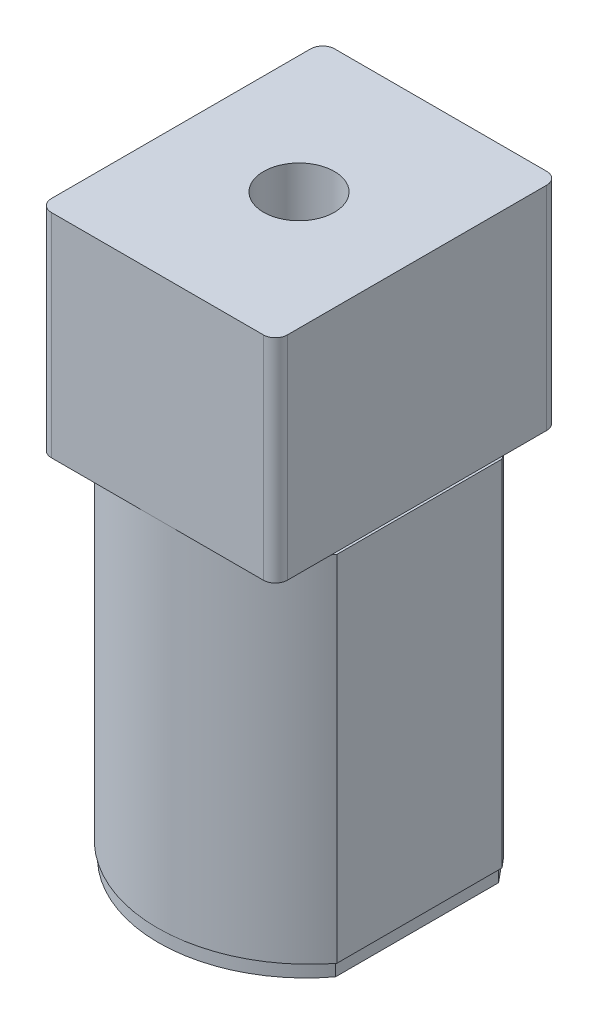
SolidWorks part; units mm, degrees
ref_plane "Front Plane" through (0, 0, 0) normal (0, 0, 1) x (1, 0, 0)
ref_plane "Top Plane" through (0, 0, 0) normal (0, 1, 0) x (1, 0, 0)
ref_plane "Right Plane" through (0, 0, 0) normal (1, 0, 0) x (0, 0, -1)
sketch "Sketch1" plane through (0, 0, 0) normal (0, 1, 0) x (1, 0, 0)
  line L0 (0, 6) -> (0, -6) construction
  line L1 (-5.1, -3.5) -> (5.1, -3.5)
  line L2 (-5.1, -3.5) -> (-5.1, 3.5)
  line L3 (-5.1, 3.5) -> (5.1, 3.5)
  line L4 (5.1, -3.5) -> (5.1, 3.5)
  line L5 (-5.1, -3.5) -> (5.1, 3.5) construction
  line L6 (-5.1, 3.5) -> (5.1, -3.5) construction
  line L7 (-3.0491, 6) -> (3.0491, 6) construction
  line L8 (-3.762, -6) -> (3.762, -6) construction
  arc A0 (-5.1, 3.5) -> (5.1, 3.5) centre (0, -0.452) cw
  arc A1 (-5.1, -3.5) -> (5.1, -3.5) centre (0, 0.452) ccw
  point P0 (0, 0)
  point P12 (0, 6)
  point P13 (0, 0)
  point P16 (0, -6)
  dimension "D1" = 7
  dimension "D2" = 10.2
  dimension "D3" = 12
extrude "Boss-Extrude1" add sketch "Sketch1" along normal blind 15 contours L1 A1 | L1 L4 L3 L2 | A0 L3
sketch "Sketch2" plane through (0, 15, 0) normal (0, 1, 0) x (1, 0, 0)
  line L1 (-5, -6) -> (5, -6)
  line L2 (-5, -6) -> (-5, 6)
  line L3 (-5, 6) -> (5, 6)
  line L4 (5, -6) -> (5, 6)
  line L5 (-5, -6) -> (5, 6) construction
  line L6 (-5, 6) -> (5, -6) construction
  point P0 (0, 0)
  dimension "D1" = 10
  dimension "D2" = 12
extrude "Boss-Extrude2" add sketch "Sketch2" along normal blind 9
fillet "Fillet1" radius 0.508 4 edges at (-5, 19.5, 6) (5, 19.5, 6) (5, 19.5, -6) (-5, 19.5, -6)
sketch "Sketch3" plane through (0, 0, 0) normal (0, -1, 0) x (1, 0, 0)
  line L0 (0, 5.95) -> (0, -5.95) construction
  line L1 (-5, -3.45) -> (5, -3.45)
  line L2 (-5, -3.45) -> (-5, 3.45)
  line L3 (-5, 3.45) -> (5, 3.45)
  line L4 (5, -3.45) -> (5, 3.45)
  line L5 (-5, -3.45) -> (5, 3.45) construction
  line L6 (-5, 3.45) -> (5, -3.45) construction
  line L7 (-1.8609, 5.95) -> (1.8609, 5.95) construction
  line L8 (-2.5738, -5.95) -> (2.5738, -5.95) construction
  arc A0 (-5, 3.45) -> (5, 3.45) centre (0, -0.3) cw
  arc A1 (-5, -3.45) -> (5, -3.45) centre (0, 0.3) ccw
  point P0 (0, 0)
  point P11 (0, 5.95)
  point P12 (0, 0)
  point P15 (0, -5.95)
  point P17 (0, 0)
  arc M2 (5.1, 3.5) -> (-5.1, 3.5) centre (0, -0.452) ccw
  line M3 (-5.1, 3.5) -> (-5.1, -3.5)
  arc M4 (-5.1, -3.5) -> (5.1, -3.5) centre (0, 0.452) ccw
  line M5 (5.1, -3.5) -> (5.1, 3.5)
  dimension "D1" = 6.9
  dimension "D2" = 10
  dimension "D3" = 11.9
extrude "Boss-Extrude3" add sketch "Sketch3" along normal blind 0.57 contours L3 M2 | L3 L1 M3 M5 | L1 M4
sketch "Sketch4" plane through (0, 24, 0) normal (0, 1, 0) x (1, 0, 0)
  circle A0 centre (0, 0) radius 1.5
  dimension "D1" = 3
extrude "Cut-Extrude1" cut sketch "Sketch4" against normal blind 8.952
